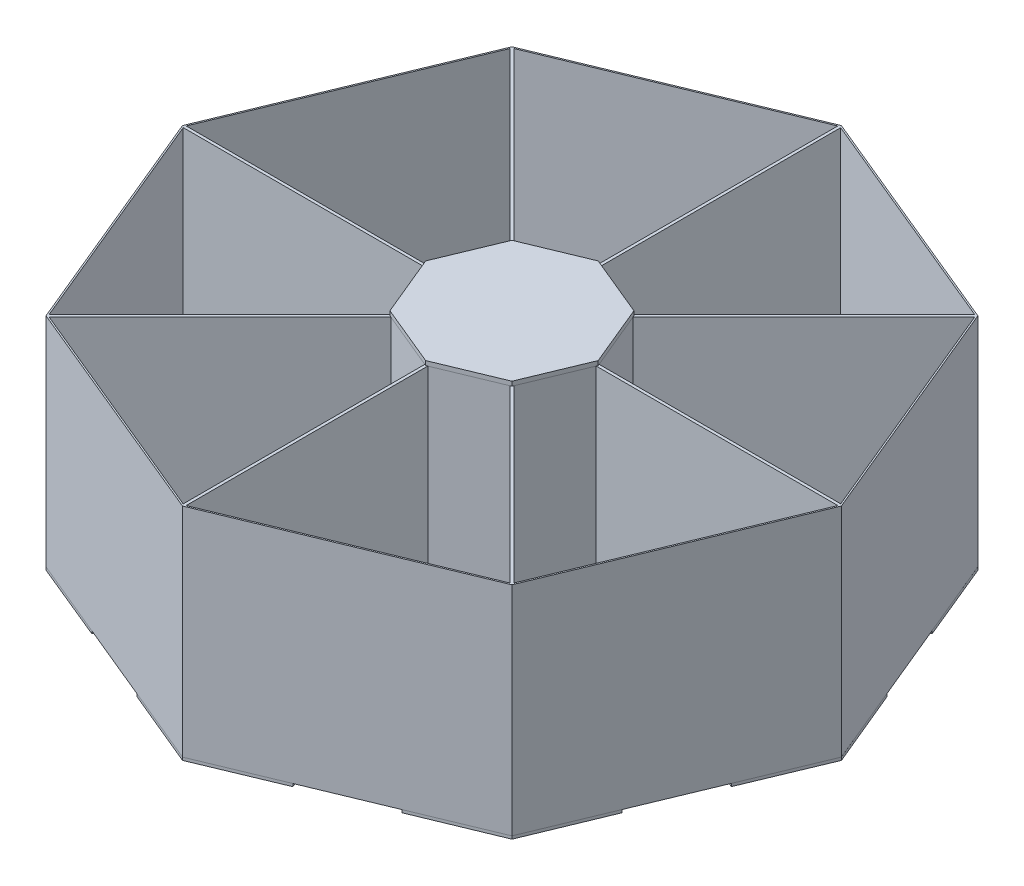
SolidWorks part; units mm, degrees
ref_plane "Front Plane" through (0, 0, 0) normal (0, 0, 1) x (1, 0, 0)
ref_plane "Top Plane" through (0, 0, 0) normal (0, 1, 0) x (1, 0, 0)
ref_plane "Right Plane" through (0, 0, 0) normal (1, 0, 0) x (0, 0, -1)
sketch "Sketch1" plane through (0, 0, 0) normal (0, 1, 0) x (1, 0, 0)
  line L0 (0, 58.423) -> (-41.273, 41.3271)
  line L1 (-1, 59.0911) -> (-41.0383, 42.5067)
  line L2 (-42.4525, 41.0925) -> (-59.037, 1.0542)
  line L3 (-59.037, -0.9458) -> (-42.4525, -40.9842)
  line L4 (-41.0383, -42.3984) -> (-1, -58.9828)
  line L5 (1, -58.9828) -> (41.0383, -42.3984)
  line L6 (42.4525, -40.9842) -> (59.037, -0.9458)
  line L7 (59.037, 1.0542) -> (42.4525, 41.0925)
  line L8 (41.0383, 42.5067) -> (1, 59.0911)
  line L9 (-1, 225.7478) -> (-158.8824, 160.3508)
  line L10 (-160.319, 158.959) -> (-225.7254, 1.0542)
  line L11 (-225.7702, -0.9458) -> (-160.3508, -158.8824)
  line L12 (-158.959, -160.319) -> (-1, -225.7478)
  line L13 (1, -225.7478) -> (158.959, -160.319)
  line L14 (160.3508, -158.8824) -> (225.7702, -0.9458)
  line L15 (225.7254, 1.0542) -> (160.319, 158.959)
  line L16 (158.8824, 160.3508) -> (1, 225.7478)
  line L17 (-41.273, 41.3271) -> (-58.3688, 0.0542)
  line L18 (-58.3688, 0.0542) -> (-41.273, -41.2188)
  line L19 (-41.273, -41.2188) -> (0, -58.3146)
  line L20 (0, -58.3146) -> (41.273, -41.2188)
  line L21 (41.273, -41.2188) -> (58.3688, 0.0542)
  line L22 (58.3688, 0.0542) -> (41.273, 41.3271)
  line L23 (41.273, 41.3271) -> (0, 58.423)
  line L24 (160.6861, 160.6861) -> (0, 227.2444)
  line L25 (0, 227.2444) -> (-160.6861, 160.6861)
  line L26 (-160.6861, 160.6861) -> (-227.2444, 0)
  line L27 (-227.2444, 0) -> (-160.6861, -160.6861)
  line L28 (-160.6861, -160.6861) -> (0, -227.2444)
  line L29 (0, -227.2444) -> (160.6861, -160.6861)
  line L30 (160.6861, -160.6861) -> (227.2444, 0)
  line L31 (227.2444, 0) -> (160.6861, 160.6861)
  line L32 (-1, -58.9828) -> (-1, -225.7478)
  line L33 (1, -58.9828) -> (1, -225.7478)
  line L34 (0, -59.397) -> (0, -226.162) construction
  line L35 (-42.4525, -40.9842) -> (-160.3732, -158.9048)
  line L36 (0, -59.397) -> (42.0383, -41.9842) construction
  line L37 (-42.0383, -41.9842) -> (0, -59.397) construction
  line L38 (0, -226.162) -> (159.9207, -159.9207) construction
  line L39 (-159.9207, -159.9207) -> (0, -226.162) construction
  line L40 (-41.0383, -42.3984) -> (-158.959, -160.319)
  line L41 (-59.037, 1.0542) -> (-225.802, 1.0542)
  line L42 (-59.037, -0.9458) -> (-225.802, -0.9458)
  line L43 (-41.0383, 42.5067) -> (-158.959, 160.4274)
  line L44 (-42.4525, 41.0925) -> (-160.3732, 159.0132)
  line L45 (1, 59.0911) -> (1, 225.8561)
  line L46 (-1, 59.0911) -> (-1, 225.8561)
  line L47 (42.4525, 41.0925) -> (160.3732, 159.0132)
  line L48 (41.0383, 42.5067) -> (158.959, 160.4274)
  line L49 (59.037, -0.9458) -> (225.802, -0.9458)
  line L50 (59.037, 1.0542) -> (225.802, 1.0542)
  line L51 (41.0383, -42.3984) -> (158.959, -160.319)
  line L52 (42.4525, -40.9842) -> (160.3732, -158.9048)
  line L54 (-59.4512, 0.0542) -> (-42.0383, -41.9842) construction
  line L55 (-42.0383, 42.0925) -> (-59.4512, 0.0542) construction
  line L56 (0, 59.5054) -> (-42.0383, 42.0925) construction
  line L57 (42.0383, 42.0925) -> (0, 59.5054) construction
  line L58 (59.4512, 0.0542) -> (42.0383, 42.0925) construction
  line L59 (42.0383, -41.9842) -> (59.4512, 0.0542) construction
  line L60 (-159.9207, 159.9207) -> (-226.162, 0) construction
  line L61 (-226.162, 0) -> (-159.9207, -159.9207) construction
  line L62 (0, 226.162) -> (-159.9207, 159.9207) construction
  line L63 (159.9207, 159.9207) -> (0, 226.162) construction
  line L64 (226.162, 0) -> (159.9207, 159.9207) construction
  line L65 (159.9207, -159.9207) -> (226.162, 0) construction
  circle A1 centre (0, 0) radius 208.9465 construction
  dimension "D1" = 107.8515
  dimension "D2" = 154
  dimension "D5" = 2
  dimension "D3" = 1
  dimension "D4" = 1
  dimension "D6" = 8
extrude "Boss-Extrude1" add sketch "Sketch1" along normal blind 150
sketch "Sketch2" plane through (0, 150, 0) normal (0, 1, 0) x (1, 0, 0)
  line L0 (-1, 59.0911) -> (-41.0383, 42.5067) construction
  line L1 (0, 59.5054) -> (-42.0766, 42.0766)
  line L2 (-42.0766, 42.0766) -> (-59.5054, 0)
  line L3 (-59.5054, 0) -> (-42.0766, -42.0766)
  line L4 (-42.0766, -42.0766) -> (0, -59.5054)
  line L5 (0, -59.5054) -> (42.0766, -42.0766)
  line L6 (42.0766, -42.0766) -> (59.5054, 0)
  line L7 (59.5054, 0) -> (42.0766, 42.0766)
  line L8 (42.0766, 42.0766) -> (0, 59.5054)
  circle A0 centre (0, 0) radius 54.9758 construction
extrude "Boss-Extrude2" add sketch "Sketch2" along normal blind 3
sketch "Sketch4" plane through (0, 0, 0) normal (0, -1, 0) x (1, 0, 0)
  line L0 (-43.2316, 39.1414) -> (-178.7966, 100.6625)
  line L1 (-193.9652, 80.343) -> (-72.7845, 30.1483) construction
  line L2 (-227.2444, 0) -> (-160.6861, 160.6861) construction
  line L3 (-58.2465, 2.8922) -> (-197.6074, 55.2491)
  line L5 (-227.2444, 0) -> (-59.4246, 0)
  line L6 (-59.4246, 0) -> (-58.2465, 2.8922)
  line L7 (0, 0) -> (0, 49.953) construction
  line L8 (-199.0943, 51.2913) -> (-197.6074, 55.2491)
  line L9 (-42.0196, 42.0196) -> (-43.2316, 39.1414)
  line L10 (-160.6861, 160.6861) -> (-42.0196, 42.0196)
  line L11 (-182.8614, 106.9091) -> (-160.6861, 160.6861)
  line L12 (-182.8614, 106.9091) -> (-177.0494, 104.5125)
  line L13 (-177.0494, 104.5125) -> (-178.7966, 100.6625)
  line L14 (-204.8987, 53.7063) -> (-199.0943, 51.2913)
  line L15 (-204.8987, 53.7063) -> (-227.2444, 0)
  dimension "D1" = 62.1427
  dimension "D2" = 2
  dimension "D3" = 67.5
  dimension "D4" = 2
extrude "Boss-Extrude3" add sketch "Sketch4" along normal blind 2
pattern_circular "CirPattern1" count 8 over 360 about axis through (0, 0, -0.0542) along (0, 1, 0) of "Boss-Extrude3"
